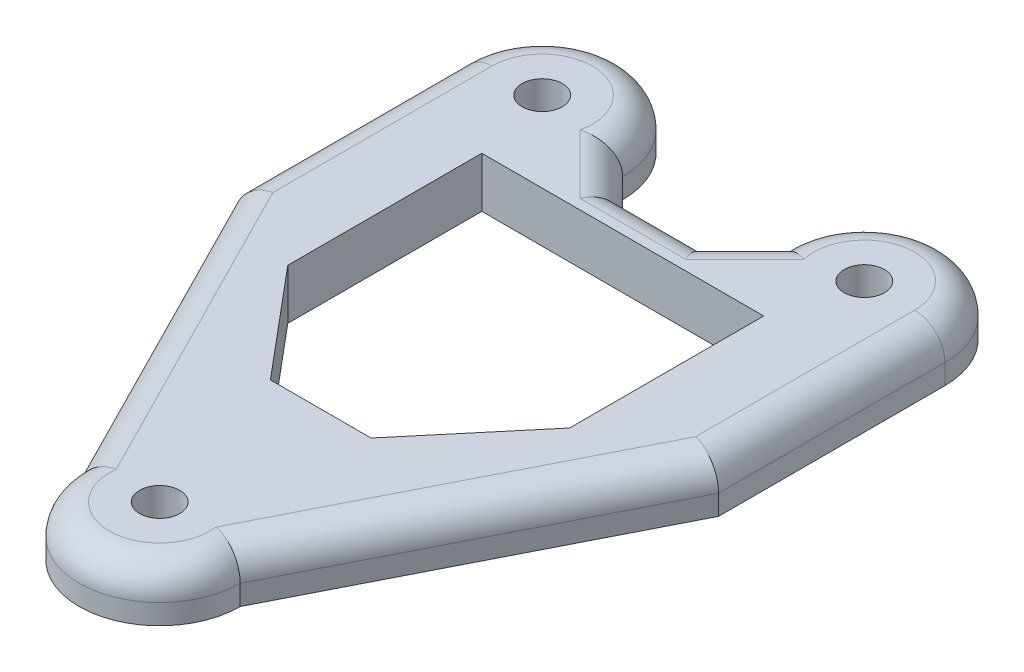
SolidWorks part; units mm, degrees
ref_plane "Front Plane" through (0, 0, 0) normal (0, 0, 1) x (1, 0, 0)
ref_plane "Top Plane" through (0, 0, 0) normal (0, 1, 0) x (1, 0, 0)
ref_plane "Right Plane" through (0, 0, 0) normal (1, 0, 0) x (0, 0, -1)
sketch "Sketch1" plane through (0, 0, 0) normal (0, 1, 0) x (1, 0, 0)
  line L0 (0.082, 8.3973) -> (0.082, 0.3973) construction
  line L5 (0.082, 0.3973) -> (72.082, 0.3973) construction
  line L6 (72.082, 0.3973) -> (72.082, 8.3973) construction
  line L7 (0.082, 8.3973) -> (72.082, 8.3973) construction
  line L8 (0.082, 38.3973) -> (0.082, 46.3973) construction
  line L9 (0.082, 46.3973) -> (72.082, 46.3973) construction
  line L10 (72.082, 46.3973) -> (72.082, 38.3973) construction
  line L11 (72.082, 38.3973) -> (0.082, 38.3973) construction
  line L12 (20.082, 46.3973) -> (20.082, 38.3973) construction
  line L13 (52.082, 46.3973) -> (52.082, 38.3973) construction
  line L14 (20.082, 8.3973) -> (20.082, 0.3973) construction
  line L15 (52.082, 8.3973) -> (52.082, 0.3973) construction
  line L16 (72.082, 38.3973) -> (72.082, 8.3973) construction
  line L21 (36.082, 8.3973) -> (36.082, -22.6027) construction
  line L22 (27.582, -7.6027) -> (44.582, -7.6027) construction
  line L23 (28.082, -7.6027) -> (12.082, 23.9202)
  line L24 (60.082, 46.3973) -> (60.082, 39.1331)
  line L25 (12.082, 23.9202) -> (12.082, 46.7397)
  line L26 (12.082, 46.7397) -> (12.082, 39.7461)
  line L27 (44.082, -7.6027) -> (60.082, 23.9202)
  line L28 (60.082, 23.9202) -> (60.082, 42.7652)
  line L29 (28.082, 46.3973) -> (32.082, 42.3973)
  line L30 (40.082, 42.3973) -> (44.082, 46.3973)
  line L31 (32.082, 42.3973) -> (40.082, 42.3973)
  line L32 (22.082, 38.3973) -> (22.082, 19.1231)
  line L33 (50.082, 38.3973) -> (50.082, 19.1231)
  line L34 (36.082, 38.3973) -> (36.082, 8.3973) construction
  line L35 (36.082, 8.3973) -> (31.082, 8.3973)
  line L36 (31.082, 8.3973) -> (22.082, 19.1231)
  line L37 (36.082, 8.3973) -> (41.082, 8.3973)
  line L38 (41.082, 8.3973) -> (50.082, 19.1231)
  line L39 (22.082, 38.3973) -> (50.082, 38.3973)
  circle A4 centre (52.082, 46.3973) radius 2
  circle A5 centre (20.082, 46.3973) radius 2
  circle A6 centre (36.082, -7.6027) radius 2
  circle A7 centre (36.082, 46.3973) radius 3 construction
  arc A8 (28.082, 46.3973) -> (12.082, 46.3973) centre (20.082, 46.3973) ccw
  arc A9 (60.082, 46.3973) -> (44.082, 46.3973) centre (52.082, 46.3973) ccw
  arc A10 (28.082, -7.6027) -> (44.082, -7.6027) centre (36.082, -7.6027) ccw
  point P4 (36.082, 38.3973)
  dimension "D7" = 4
  dimension "D1" = 8
  dimension "D2" = 8
  dimension "D3" = 20
  dimension "D4" = 20
  dimension "D5" = 20
  dimension "D6" = 20
  dimension "D8" = 8
  dimension "D10" = 8
  dimension "D9" = 32
  dimension "D11" = 30
  dimension "D12" = 14
  dimension "D13" = 5
  dimension "D14" = 130
  dimension "D15" = 116.911
extrude "Boss-Extrude1" add sketch "Sketch1" along normal blind 5 contours L23 A10 L27 L28 L24 A9 L30 L31 L29 A8 L25 L32 L39 L33 L38 L37 L35 L36 A4 A5 A6
fillet "Fillet2" radius 3 10 edges at (52.082, 5, -54.3973) (42.082, 5, -44.3973) (36.082, 5, -42.3973) (30.082, 5, -44.3973) (20.082, 5, -54.3973) (12.082, 5, -35.1588) (20.082, 5, -8.1588) (36.082, 5, 15.6027) (52.082, 5, -8.1588) (60.082, 5, -35.1588)
equation "\"D13@Sketch1\"=10/2"
